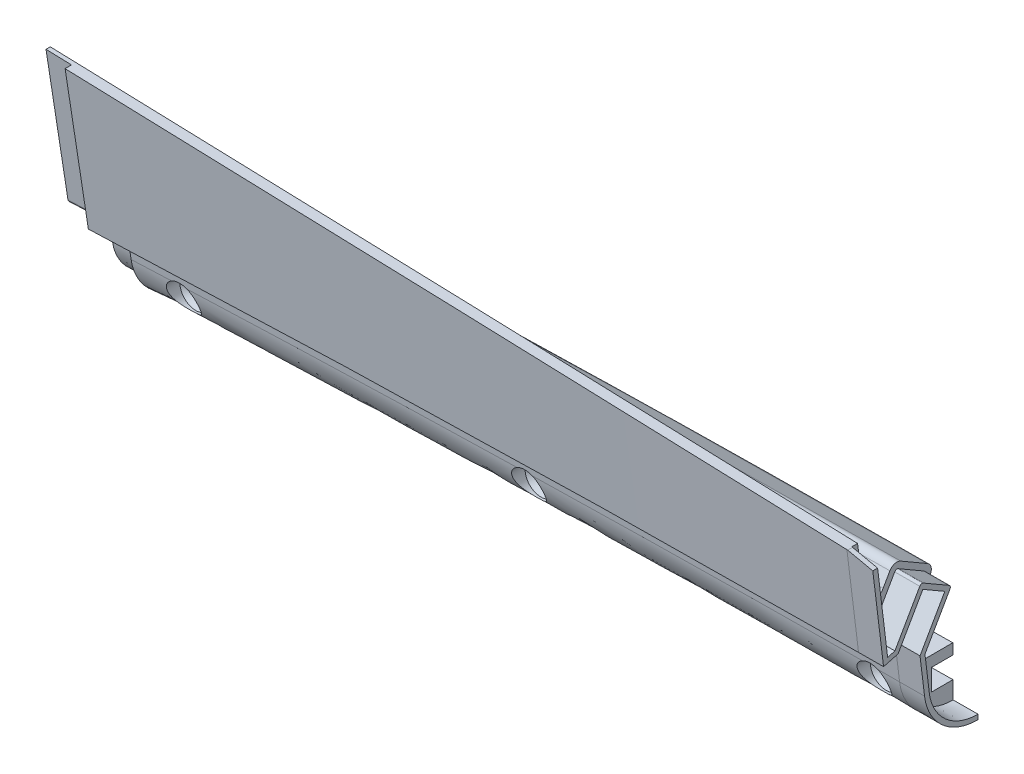
SolidWorks part; units mm, degrees
ref_plane "Front Plane" through (0, 0, 0) normal (0, 0, 1) x (1, 0, 0)
ref_plane "Top Plane" through (0, 0, 0) normal (0, 1, 0) x (1, 0, 0)
ref_plane "Right Plane" through (0, 0, 0) normal (1, 0, 0) x (0, 0, -1)
ref_plane "Plane3" through (-117.056, -3.871, 0) normal (0.9995, 0.0331, 0) x (0, 0, -1)
sketch "Sketch2" plane through (-117.056, -3.871, 0) normal (0.9995, 0.0331, 0) x (0, 0, -1)
  line L0 (-101.6, -41.1511) -> (-101.6, -45.9265)
  line L1 (-101.6, -41.1511) -> (-101.6, -45.9265)
  line L2 (-106.68, -45.9265) -> (-106.68, -50.6257)
  line L3 (-106.68, -45.9265) -> (-106.68, -50.6257)
  line L4 (-101.6, -50.6257) -> (-106.68, -50.6257)
  line L5 (-101.6, -50.6257) -> (-106.68, -50.6257)
  line L6 (-101.6, -50.6257) -> (-101.6, -56.1377)
  line L7 (-101.6, -50.6257) -> (-101.6, -56.1377)
  line L8 (-106.68, -45.9265) -> (-101.6, -45.9265)
  line L9 (-106.68, -45.9265) -> (-101.6, -45.9265)
  line L10 (-106.8705, -50.8162) -> (-108.9961, -53.9781) construction
  line L11 (-101.7905, -43.196) -> (-101.7905, -45.736)
  line L12 (-106.8705, -45.736) -> (-101.7905, -45.736)
  line L13 (-106.8705, -45.736) -> (-106.8705, -50.8162)
  line L14 (-101.7905, -50.8162) -> (-106.8705, -50.8162)
  line L15 (-101.7905, -50.8162) -> (-101.7905, -56.1377)
  line L16 (-101.7905, -43.196) -> (-101.6, -43.196)
  line L17 (-101.7905, -41.1511) -> (-101.7905, -45.736) construction
  line L18 (-120.8053, -33.0481) -> (-115.57, -36.0708)
  line L19 (-120.8053, -33.0481) -> (-115.57, -36.0708)
  line L20 (-109.601, -25.7318) -> (-114.8363, -22.709)
  line L21 (-109.601, -25.7318) -> (-114.8363, -22.709)
  line L22 (-114.8363, -22.709) -> (-120.8053, -33.0481)
  line L23 (-114.8363, -22.709) -> (-120.8053, -33.0481)
  line L24 (-115.57, -36.0708) -> (-109.601, -25.7318)
  line L25 (-115.57, -36.0708) -> (-109.601, -25.7318)
  line L26 (-115.57, -36.0708) -> (-114.523, -44.9291)
  line L28 (-118.1876, -34.5595) -> (-112.2186, -24.2204) construction
  line L29 (-114.6403, -39.5406) -> (-107.0838, -26.4518)
  line L30 (-107.7811, -23.8496) -> (-114.1162, -20.1918)
  line L31 (-116.7185, -20.8891) -> (-124.2749, -33.9778)
  line L33 (-106.1314, -24.8021) -> (-115.766, -19.2393) construction
  line L34 (-115.766, -19.2393) -> (-124.2749, -33.9778) construction
  line L35 (-114.6403, -39.5406) -> (-106.1314, -24.8021) construction
  line L36 (-124.2749, -33.9778) -> (-114.6403, -39.5406) construction
  line L37 (-112.9486, -36.6103) -> (-112.1701, -43.196)
  line L38 (-124.2749, -33.9778) -> (-128.0422, -2.1051)
  line L39 (-128.0422, -2.1051) -> (-132.6063, -0.4439)
  line L40 (-50.8, 0.7495) -> (-2184.4, 0.7495)
  line L41 (-125.822, 0.7495) -> (-133.442, 0.7495)
  line L42 (-122.1519, -30.3004) -> (-125.822, 0.7495)
  arc A0 (-114.523, -44.9291) -> (-101.7905, -56.1377) centre (-101.9108, -43.4383) ccw
  arc A2 (-114.1162, -20.1918) -> (-116.7185, -20.8891) centre (-115.0687, -21.8416) ccw
  arc A3 (-107.0838, -26.4518) -> (-107.7811, -23.8496) centre (-108.7336, -25.4993) ccw
  arc A4 (-133.442, 0.7495) -> (-132.6063, -0.4439) centre (-132.172, 0.7495) ccw
  point P41 (-133.442, 0.7495)
  dimension "D2" = 25.4
  dimension "D6" = 1.905
  dimension "D8" = 2.54
  dimension "D4" = 2.54
  dimension "D5" = 2.54
  dimension "D7" = 2.54
  dimension "D9" = 2.54
  dimension "D10" = 20
  dimension "D11" = 7.62
  dimension "D12" = 3.81
  dimension "D3" = 0.1905
sketch "Sketch3" plane through (0, 0, 101.6) normal (0, 0, 1) x (1, 0, 0)
  arc A0 (622.1039, -83.1998) -> (-622.1039, -83.1998) centre (0, -4954.4862) ccw construction
  arc A1 (622.1039, -83.1998) -> (-622.1039, -83.1998) centre (0, -4954.4862) ccw
sketch "Sketch4" plane through (-117.3306, 4.4304, 1117.6) normal (0.9995, 0.0331, 0) x (0, 0, -1)
  line L29 (1009.8189, -32.1556) -> (1003.4838, -28.4978) construction
  line L32 (1000.8815, -29.1951) -> (993.3251, -42.2838) construction
  line L35 (993.3251, -42.2838) -> (989.5578, -10.4111) construction
  line L50 (995.4481, -38.6064) -> (991.778, -7.5565) construction
  line L51 (1002.03, -44.3768) -> (1003.077, -53.235) construction
  line L52 (1015.8095, -59.1222) -> (1015.8095, -64.4437) construction
  line L53 (1015.8095, -59.1222) -> (1010.7295, -59.1222) construction
  line L54 (1010.7295, -54.042) -> (1010.7295, -59.1222) construction
  line L55 (1010.7295, -54.042) -> (1015.8095, -54.042) construction
  line L56 (1015.8095, -51.502) -> (1015.8095, -54.042) construction
  line L57 (1015.8095, -51.502) -> (1016, -51.502) construction
  line L58 (1004.6514, -44.9163) -> (1005.4299, -51.502) construction
  line L60 (1002.7637, -31.015) -> (996.7947, -41.3541) construction
  line L61 (1007.999, -34.0377) -> (1002.7637, -31.015) construction
  line L62 (1002.03, -44.3768) -> (1007.999, -34.0377) construction
  line L64 (991.5295, -5.4538) -> (988.9718, -5.4538)
  line L69 (1009.8189, -32.1556) -> (1003.4838, -28.4978)
  line L70 (1000.8815, -29.1951) -> (999.2724, -31.9822)
  line L71 (993.3251, -42.2838) -> (988.9718, -5.4538)
  line L74 (994.5502, -31.0104) -> (991.5295, -5.4538)
  line L75 (1002.03, -44.3768) -> (1003.077, -53.235)
  line L76 (1015.8095, -59.1222) -> (1015.8095, -64.4437)
  line L77 (1015.8095, -59.1222) -> (1010.7295, -59.1222)
  line L78 (1010.7295, -54.042) -> (1010.7295, -59.1222)
  line L79 (1010.7295, -54.042) -> (1015.8095, -54.042)
  line L80 (1015.8095, -51.502) -> (1015.8095, -54.042)
  line L81 (1015.8095, -51.502) -> (1007.6873, -51.502)
  line L82 (1004.7505, -45.7539) -> (1005.1649, -49.2601)
  line L84 (1002.7637, -31.015) -> (996.7947, -41.3541)
  line L85 (1007.999, -34.0377) -> (1002.7637, -31.015)
  line L86 (1002.03, -44.3768) -> (1007.999, -34.0377)
  line L87 (996.7947, -41.3541) -> (993.3251, -42.2838)
  line L88 (1005.0732, -44.1858) -> (1010.5162, -34.7578)
  arc A8 (1010.5162, -34.7578) -> (1009.8189, -32.1556) centre (1008.8664, -33.8053) ccw construction
  arc A9 (1003.4838, -28.4978) -> (1000.8815, -29.1951) centre (1002.5313, -30.1476) ccw construction
  arc A11 (1003.077, -53.235) -> (1015.8095, -64.4437) centre (1015.6892, -51.7443) ccw construction
  arc A12 (1010.5162, -34.7578) -> (1009.8189, -32.1556) centre (1008.8664, -33.8053) ccw
  arc A13 (1003.4838, -28.4978) -> (1000.8815, -29.1951) centre (1002.5313, -30.1476) ccw
  arc A15 (1003.077, -53.235) -> (1015.8095, -64.4437) centre (1015.6892, -51.7443) ccw
  arc A16 (1005.1649, -49.2601) -> (1007.6873, -51.502) centre (1007.6873, -48.962) ccw
  arc A17 (1004.7505, -45.7539) -> (1005.0732, -44.1858) centre (1007.2729, -45.4558) cw
  arc A18 (994.5502, -31.0104) -> (999.2724, -31.9822) centre (997.0727, -30.7122) ccw
  dimension "D2" = 2.54
  dimension "D1" = 36.83
sweep "Sweep3" add profiles "Sketch4" path "Sketch3"
sketch "Sketch5" plane through (0, 0, 101.7905) normal (0, 0, -1) x (-1, 0, 0)
  line L0 (211.6509, -4.1577) -> (0, -4954.4862) construction
  line L1 (0, -4954.4862) -> (26.0737, -15.25) construction
  line L2 (117.0808, -1.0187) -> (0, -4954.4862) construction
  arc A1 (628.0925, -39.606) -> (-627.2635, -39.5001) centre (0, -4954.4862) ccw construction
  point P16 (117.0808, -1.0187)
ref_plane "Plane1" through (-211.4422, -9.0402, 0) normal (-0.9991, -0.0427, 0) x (0.0427, -0.9991, 0)
ref_plane "Plane2" through (-26.1535, -0.1381, 0) normal (1, 0.0053, 0) x (-0.0053, 1, 0)
other "SurfaceCut1"
other "SurfaceCut2"
sketch "Sketch8" plane through (-117.056, -3.871, 0) normal (0.9995, 0.0331, 0) x (0, 0, -1)
  line L0 (-106.8705, -50.8162) -> (-106.8705, -45.736)
  line L1 (-106.8705, -50.8162) -> (-106.8705, -45.736)
  line L2 (-106.8705, -48.2761) -> (-119.5705, -48.2761)
  line L3 (-119.5705, -48.2761) -> (-119.5705, -44.4661)
  line L4 (-119.5705, -44.4661) -> (-110.6805, -44.4661)
  line L5 (-110.6805, -44.4661) -> (-108.7755, -46.3711)
  line L6 (-108.7755, -46.3711) -> (-106.8705, -46.3711)
  line L7 (-119.5705, -48.2761) -> (-117.7248, -48.2761) construction
  dimension "D1" = 1.905
  dimension "D2" = 1.905
  dimension "D3" = 12.7
  dimension "D4" = 45
  dimension "D5" = 3.81
revolve "Cut-Revolve1" cut sketch "Sketch8" angle 360 about L7
sketch "Sketch9" plane through (0, 0, 106.8705) normal (0, 0, -1) x (-1, 0, 0)
  line L0 (198.0737, -52.2212) -> (197.8686, -57.297) construction
  line L1 (32.934, -48.3318) -> (32.8999, -53.4117) construction
  arc A1 (209.5755, -52.6994) -> (25.8993, -48.2896) centre (0, -4954.4862) ccw construction
  arc A2 (209.3585, -57.7748) -> (25.8725, -53.3695) centre (0, -4954.4862) ccw construction
  point P8 (197.9712, -54.7591)
  point P11 (0, -4954.4862)
  point P16 (115.4604, -52.1207)
  dimension "D1" = 82.55
  dimension "D2" = 82.55
sketch "Sketch10" plane through (0, 0, 106.8705) normal (0, 0, -1) x (-1, 0, 0)
  line L0 (32.934, -48.3318) -> (32.8999, -53.4117) construction
  point P0 (32.917, -50.8717)
  point P1 (197.9712, -54.7591)
pattern_sketch "Sketch-Pattern1" of "Cut-Revolve1" driven by "Sketch10"
sketch "Sketch12" plane through (0, 0, 101.7905) normal (0, 0, -1) x (-1, 0, 0)
  line L0 (25.9127, -45.7498) -> (0, -4954.4862) construction
  line L1 (0, -4954.4862) -> (19.9437, -45.7219) construction
  arc A1 (209.684, -50.1619) -> (25.9127, -45.7498) centre (0, -4954.4862) ccw construction
  arc A2 (25.9127, -45.7498) -> (19.9437, -45.7219) centre (0, -4954.4862) ccw
  dimension "D1" = 5.969
sketch "Sketch11" plane through (-26.1535, -0.1381, 0) normal (1, 0.0053, 0) x (0, 0, -1)
  line L6 (-101.7905, -53.2322) -> (-101.7905, -58.5535) construction
  line L10 (-128.6282, 0.4338) -> (-126.0705, 0.4338) construction
  line L11 (-124.2749, -36.3946) -> (-128.6282, 0.4338) construction
  line L12 (-120.8053, -35.4649) -> (-124.2749, -36.3946) construction
  line L13 (-114.8363, -25.1263) -> (-120.8053, -35.4649) construction
  line L14 (-109.601, -28.1489) -> (-114.8363, -25.1263) construction
  line L15 (-115.57, -38.4875) -> (-109.601, -28.1489) construction
  line L16 (-114.523, -47.3454) -> (-115.57, -38.4875) construction
  line L17 (-101.7905, -57.4106) -> (-101.7905, -58.5535)
  line L18 (-128.6282, 0.4338) -> (-127.4772, 0.4338)
  line L25 (-124.2749, -36.3946) -> (-128.6282, 0.4338)
  line L26 (-120.8053, -35.4649) -> (-124.2749, -36.3946)
  line L27 (-114.8363, -25.1263) -> (-120.8053, -35.4649)
  line L29 (-109.601, -28.1489) -> (-114.8363, -25.1263)
  line L30 (-115.57, -38.4875) -> (-109.601, -28.1489)
  line L31 (-114.523, -47.3454) -> (-115.57, -38.4875)
  line L32 (-113.3879, -47.2112) -> (-114.3903, -38.7303)
  line L33 (-114.3903, -38.7303) -> (-108.3571, -28.2805)
  line L34 (-108.5896, -27.4131) -> (-114.7047, -23.8825)
  line L35 (-115.5722, -24.1149) -> (-121.5584, -34.4834)
  line L54 (-121.5584, -34.4834) -> (-123.2949, -34.9487)
  line L55 (-123.2949, -34.9487) -> (-127.4772, 0.4338)
  line L56 (-101.8013, -57.4106) -> (-101.7905, -57.4106)
  line L57 (-123.2949, -34.9487) -> (-127.4931, 0.568) construction
  line L58 (-114.3903, -38.7303) -> (-108.0396, -27.7306) construction
  line L59 (-108.0396, -27.7306) -> (-115.2547, -23.565) construction
  line L60 (-115.2547, -23.565) -> (-121.5584, -34.4834) construction
  arc A2 (-108.3571, -28.2805) -> (-108.5896, -27.4131) centre (-108.9071, -27.963) ccw
  arc A3 (-114.7047, -23.8825) -> (-115.5722, -24.1149) centre (-115.0222, -24.4324) ccw
  spline S0 degree 3 poles (369.46, 1883.5044) (53.4107, 251.0151) (-51.656, -67.5371) (-104.4782, -58.2978) (-104.8546, -58.2143) (-105.6018, -58.0121) (-105.9744, -57.8927) (-107.0674, -57.4861) (-107.762, -57.1522) (-108.7542, -56.5596) (-109.0766, -56.3467) (-109.7043, -55.8893) (-110.0099, -55.6443) (-110.8822, -54.8766) (-111.4114, -54.3174) (-112.3662, -53.1048) (-112.7943, -52.4449) (-113.513, -51.0771) (-113.8076, -50.3659) (-114.1523, -49.2581) (-114.2511, -48.8807) (-128.7728, 19.3226) (415.3179, 185.4408) (1806.7101, 500.6763) knots -8.519335 -8.519335 -8.519335 -8.519335 0.125 0.125 0.1875 0.1875 0.25 0.25 0.375 0.375 0.4375 0.4375 0.5 0.5 0.625 0.625 0.75 0.75 0.875 0.875 0.9375 0.9375 12.048429 12.048429 12.048429 12.048429 only from (-101.7905, -58.5535) to (-114.523, -47.3454) construction
  spline S1 degree 3 poles (-101.7905, -58.5535) (-102.5713, -58.5609) (-103.3407, -58.4968) (-104.4782, -58.2978) (-104.8546, -58.2143) (-105.6018, -58.0121) (-105.9744, -57.8927) (-107.0674, -57.4861) (-107.762, -57.1522) (-108.7542, -56.5596) (-109.0766, -56.3467) (-109.7043, -55.8893) (-110.0099, -55.6443) (-110.8822, -54.8766) (-111.4114, -54.3174) (-112.3662, -53.1048) (-112.7943, -52.4449) (-113.513, -51.0771) (-113.8076, -50.3659) (-114.1523, -49.2581) (-114.2511, -48.8807) (-114.4136, -48.1177) (-114.4771, -47.7331) (-114.523, -47.3454) knots 0 0 0 0 0.125 0.125 0.1875 0.1875 0.25 0.25 0.375 0.375 0.4375 0.4375 0.5 0.5 0.625 0.625 0.75 0.75 0.875 0.875 0.9375 0.9375 1 1 1 1
  spline S2 degree 1 poles (-101.8013, -57.4106) (-113.3879, -47.2112) knots 0 0 1 1 construction
  spline S3 degree 3 poles (-101.8013, -57.4106) (-103.2019, -57.4238) (-106.0351, -56.929) (-109.7159, -54.7282) (-111.9316, -51.9047) (-113.0054, -49.3139) (-113.3048, -47.914) (-113.3879, -47.2112) knots 0 0 0 0 0.25 0.5 0.75 0.875 1 1 1 1
  dimension "D2" = 0.635
  dimension "D1" = 1.143
sweep "Sweep4" add profiles "Sketch11" path "Sketch12"
sketch "Sketch14" plane through (-211.4422, -9.0402, 0) normal (-0.9991, -0.0427, 0) x (0, 0, 1)
  line L0 (113.0095, -42.7133) -> (113.9971, -34.3581)
  line L1 (113.9971, -34.3581) -> (107.5192, -23.138)
  line L2 (107.5192, -23.138) -> (115.3941, -18.5914)
  line L3 (115.3941, -18.5914) -> (121.8095, -29.7031)
  line L4 (121.8095, -29.7031) -> (122.9682, -30.0136)
  line L5 (122.9682, -30.0136) -> (127.1147, 5.0658)
  line L18 (128.6282, 4.8869) -> (126.0705, 4.8869)
  line L19 (126.0705, 4.8869) -> (123.0498, -20.6686)
  line L20 (118.3276, -21.6403) -> (116.7185, -18.8534)
  line L21 (114.1162, -18.1561) -> (107.7811, -21.8137)
  line L22 (107.0838, -24.4158) -> (112.5268, -33.8434)
  line L23 (112.8495, -35.4115) -> (112.4351, -38.9175)
  line L24 (109.9127, -41.1592) -> (101.7905, -41.1592)
  line L25 (101.7905, -41.1592) -> (101.7905, -43.6991)
  line L26 (101.7905, -43.6991) -> (106.8705, -43.6991)
  line L27 (106.8705, -43.6991) -> (106.8705, -48.7791)
  line L28 (106.8705, -48.7791) -> (101.7905, -48.7791)
  line L29 (101.7905, -48.7791) -> (101.7905, -54.1004)
  line L30 (114.523, -42.8922) -> (115.57, -34.0344)
  line L31 (115.57, -34.0344) -> (109.601, -23.6958)
  line L32 (109.601, -23.6958) -> (114.8363, -20.6732)
  line L33 (114.8363, -20.6732) -> (120.8053, -31.0118)
  line L34 (120.8053, -31.0118) -> (124.2749, -31.9414)
  line L35 (124.2749, -31.9414) -> (128.6282, 4.8869)
  line L36 (128.6282, 4.8869) -> (126.0705, 4.8869)
  line L37 (126.0705, 4.8869) -> (123.0498, -20.6686)
  line L38 (118.3276, -21.6403) -> (116.7185, -18.8534)
  line L39 (114.1162, -18.1561) -> (107.7811, -21.8137)
  line L40 (107.0838, -24.4158) -> (112.5268, -33.8434)
  line L41 (112.8495, -35.4115) -> (112.4351, -38.9175)
  line L42 (109.9127, -41.1592) -> (101.7905, -41.1592)
  line L43 (101.7905, -41.1592) -> (101.7905, -43.6991)
  line L44 (101.7905, -43.6991) -> (106.8705, -43.6991)
  line L45 (106.8705, -43.6991) -> (106.8705, -48.7791)
  line L46 (106.8705, -48.7791) -> (101.7905, -48.7791)
  line L47 (101.7905, -48.7791) -> (101.7905, -54.1004)
  line L48 (114.523, -42.8922) -> (115.57, -34.0344)
  line L49 (115.57, -34.0344) -> (109.601, -23.6958)
  line L50 (109.601, -23.6958) -> (114.8363, -20.6732)
  line L51 (114.8363, -20.6732) -> (120.8053, -31.0118)
  line L52 (120.8053, -31.0118) -> (124.2749, -31.9414)
  line L53 (124.2749, -31.9414) -> (128.6282, 4.8869)
  arc A4 (116.7185, -18.8534) -> (114.1162, -18.1561) centre (115.0687, -19.8059) ccw
  arc A5 (107.7811, -21.8137) -> (107.0838, -24.4158) centre (108.7335, -23.4634) ccw
  arc A6 (112.8495, -35.4115) -> (112.5268, -33.8434) centre (110.3273, -35.1133) ccw
  arc A7 (109.9127, -41.1592) -> (112.4351, -38.9175) centre (109.9127, -38.6193) ccw
  arc A8 (116.7185, -18.8534) -> (114.1162, -18.1561) centre (115.0687, -19.8059) ccw
  arc A9 (107.7811, -21.8137) -> (107.0838, -24.4158) centre (108.7335, -23.4634) ccw
  arc A10 (112.8495, -35.4115) -> (112.5268, -33.8434) centre (110.3273, -35.1133) ccw
  arc A11 (109.9127, -41.1592) -> (112.4351, -38.9175) centre (109.9127, -38.6193) ccw
  spline S0 degree 1 poles (101.8049, -52.5765) (113.0095, -42.7133) knots 0 0 1 1 construction
  spline S1 degree 3 poles (101.8049, -52.5765) (102.4893, -52.583) (103.8689, -52.4674) (106.4858, -51.7551) (109.4658, -49.9761) (112.0284, -46.7154) (112.8505, -44.0584) (113.0095, -42.7133) knots 0 0 0 0 0.125 0.25 0.5 0.75 1 1 1 1
  spline S2 degree 3 poles (-1420.2451, -2589.1907) (7.5348, 76.4537) (129.3579, -7.252) (122.7249, -21.671) (122.575, -21.8961) (122.2185, -22.2837) (122.0069, -22.4517) (121.6628, -22.6462) (121.5435, -22.702) (121.2955, -22.795) (121.1665, -22.8321) (120.908, -22.8851) (120.7774, -22.9014) (120.5134, -22.9137) (120.3791, -22.9094) (120.1163, -22.8803) (119.987, -22.8557) (119.7325, -22.7864) (119.6063, -22.7412) (119.2436, -22.578) (119.0214, -22.433) (93.7379, 0.421) (581.1886, 448.0858) (2362.312, 1968.4478) knots -7.286241 -7.286241 -7.286241 -7.286241 0.125 0.125 0.25 0.25 0.375 0.375 0.4375 0.4375 0.5 0.5 0.5625 0.5625 0.625 0.625 0.6875 0.6875 0.75 0.75 0.875 0.875 16.766809 16.766809 16.766809 16.766809 only from (123.0498, -20.6686) to (118.3276, -21.6403)
  spline S3 degree 3 poles (-288.3388, 2916.9987) (-102.777, 757.3692) (19.5454, -60.9671) (103.3479, -54.0254) (103.7348, -53.9753) (104.8774, -53.7738) (105.6202, -53.5717) (107.068, -53.0324) (107.777, -52.6914) (109.1008, -51.8981) (109.7227, -51.4442) (110.5948, -50.6762) (110.8766, -50.4042) (111.4099, -49.8396) (111.662, -49.5468) (112.3757, -48.6378) (112.795, -47.9912) (113.3369, -46.9586) (113.5026, -46.6041) (113.7979, -45.8886) (113.9285, -45.5258) (132.5439, 14.5864) (-288.4354, 203.7302) (-2703.1014, 979.8882) knots -13.349036 -13.349036 -13.349036 -13.349036 0.0625 0.0625 0.125 0.125 0.25 0.25 0.375 0.375 0.5 0.5 0.5625 0.5625 0.625 0.625 0.75 0.75 0.8125 0.8125 0.875 0.875 11.030088 11.030088 11.030088 11.030088 only from (101.7905, -54.1004) to (114.523, -42.8922)
  spline S4 degree 3 poles (123.0498, -20.6686) (123.0184, -20.9338) (122.9449, -21.1927) (122.7249, -21.671) (122.575, -21.8961) (122.2185, -22.2837) (122.0069, -22.4517) (121.6628, -22.6462) (121.5435, -22.702) (121.2955, -22.795) (121.1665, -22.8321) (120.908, -22.8851) (120.7774, -22.9014) (120.5134, -22.9137) (120.3791, -22.9094) (120.1163, -22.8803) (119.987, -22.8557) (119.7325, -22.7864) (119.6063, -22.7412) (119.2436, -22.578) (119.0214, -22.433) (118.6267, -22.0763) (118.4611, -21.8716) (118.3276, -21.6403) knots 0 0 0 0 0.125 0.125 0.25 0.25 0.375 0.375 0.4375 0.4375 0.5 0.5 0.5625 0.5625 0.625 0.625 0.6875 0.6875 0.75 0.75 0.875 0.875 1 1 1 1
  spline S5 degree 3 poles (101.7905, -54.1004) (102.1809, -54.1041) (102.5705, -54.0898) (103.3479, -54.0254) (103.7348, -53.9753) (104.8774, -53.7738) (105.6202, -53.5717) (107.068, -53.0324) (107.777, -52.6914) (109.1008, -51.8981) (109.7227, -51.4442) (110.5948, -50.6762) (110.8766, -50.4042) (111.4099, -49.8396) (111.662, -49.5468) (112.3757, -48.6378) (112.795, -47.9912) (113.3369, -46.9586) (113.5026, -46.6041) (113.7979, -45.8886) (113.9285, -45.5258) (114.2702, -44.4227) (114.4313, -43.6677) (114.523, -42.8922) knots 0 0 0 0 0.0625 0.0625 0.125 0.125 0.25 0.25 0.375 0.375 0.5 0.5 0.5625 0.5625 0.625 0.625 0.75 0.75 0.8125 0.8125 0.875 0.875 1 1 1 1
  dimension "D1" = 0
  dimension "D2" = 1.524
sketch "Sketch15" plane through (-211.4422, -9.0402, 0) normal (-0.9991, -0.0427, 0) x (0, 0, 1)
  line L0 (113.0095, -42.7133) -> (113.9971, -34.3581) construction
  line L1 (113.9971, -34.3581) -> (107.5192, -23.138) construction
  line L2 (107.5192, -23.138) -> (115.3941, -18.5914) construction
  line L3 (115.3941, -18.5914) -> (121.8095, -29.7031) construction
  line L4 (121.8095, -29.7031) -> (122.9682, -30.0136) construction
  line L5 (122.9682, -30.0136) -> (127.1147, 5.0658) construction
  line L6 (113.0095, -42.7133) -> (113.9724, -34.5675)
  line L7 (113.8917, -34.1755) -> (107.5192, -23.138)
  line L8 (107.5192, -23.138) -> (115.3941, -18.5914)
  line L9 (115.3941, -18.5914) -> (121.678, -29.4753)
  line L10 (122.0636, -29.7712) -> (122.2594, -29.8237)
  line L11 (123.0543, -29.2848) -> (127.0936, 4.8869)
  line L12 (101.7905, -48.7791) -> (101.7905, -54.1004) construction
  line L13 (101.7905, -48.7791) -> (101.7905, -52.5765)
  line L14 (101.8049, -52.5765) -> (101.7905, -52.5765)
  line L18 (124.2749, -31.9414) -> (128.6282, 4.8869)
  line L19 (128.6282, 4.8869) -> (126.0705, 4.8869)
  line L20 (126.0705, 4.8869) -> (123.0498, -20.6686)
  line L21 (118.3276, -21.6403) -> (116.7185, -18.8534)
  line L22 (114.1162, -18.1561) -> (107.7811, -21.8137)
  line L23 (107.0838, -24.4158) -> (112.5268, -33.8434)
  line L24 (112.8495, -35.4115) -> (112.4351, -38.9175)
  line L25 (109.9127, -41.1592) -> (101.7905, -41.1592)
  line L26 (101.7905, -41.1592) -> (101.7905, -43.6991)
  line L27 (101.7905, -43.6991) -> (106.8705, -43.6991)
  line L28 (106.8705, -43.6991) -> (106.8705, -48.7791)
  line L29 (106.8705, -48.7791) -> (101.7905, -48.7791)
  line L30 (101.7905, -48.7791) -> (101.7905, -54.1004)
  line L31 (114.523, -42.8922) -> (115.57, -34.0344)
  line L32 (115.57, -34.0344) -> (109.601, -23.6958)
  line L33 (109.601, -23.6958) -> (114.8363, -20.6732)
  line L34 (114.8363, -20.6732) -> (120.8053, -31.0118)
  line L35 (120.8053, -31.0118) -> (124.2749, -31.9414)
  line L37 (127.0936, 4.8869) -> (126.0705, 4.8869)
  line L38 (126.0705, 4.8869) -> (123.0498, -20.6686)
  line L39 (118.3276, -21.6403) -> (116.7185, -18.8534)
  line L40 (114.1162, -18.1561) -> (107.7811, -21.8137)
  line L41 (107.0838, -24.4158) -> (112.5268, -33.8434)
  line L42 (112.8495, -35.4115) -> (112.4351, -38.9175)
  line L43 (109.9127, -41.1592) -> (101.7905, -41.1592)
  line L44 (101.7905, -41.1592) -> (101.7905, -43.6991)
  line L45 (101.7905, -43.6991) -> (106.8705, -43.6991)
  line L46 (106.8705, -43.6991) -> (106.8705, -48.7791)
  line L47 (106.8705, -48.7791) -> (101.7905, -48.7791)
  arc A0 (113.9724, -34.5675) -> (113.8917, -34.1755) centre (113.3418, -34.493) ccw
  arc A1 (121.678, -29.4753) -> (122.0636, -29.7712) centre (122.2279, -29.1578) ccw
  arc A2 (122.2594, -29.8237) -> (123.0543, -29.2848) centre (122.4237, -29.2103) ccw
  arc A4 (116.7185, -18.8534) -> (114.1162, -18.1561) centre (115.0687, -19.8059) ccw
  arc A5 (107.7811, -21.8137) -> (107.0838, -24.4158) centre (108.7335, -23.4634) ccw
  arc A6 (112.8495, -35.4115) -> (112.5268, -33.8434) centre (110.3273, -35.1133) ccw
  arc A7 (109.9127, -41.1592) -> (112.4351, -38.9175) centre (109.9127, -38.6193) ccw
  arc A8 (116.7185, -18.8534) -> (114.1162, -18.1561) centre (115.0687, -19.8059) ccw
  arc A9 (107.7811, -21.8137) -> (107.0838, -24.4158) centre (108.7335, -23.4634) ccw
  arc A10 (112.8495, -35.4115) -> (112.5268, -33.8434) centre (110.3273, -35.1133) ccw
  arc A11 (109.9127, -41.1592) -> (112.4351, -38.9175) centre (109.9127, -38.6193) ccw
  spline S0 degree 3 poles (1969.6766, 654.3437) (8.5109, 56.766) (75.3403, -60.2329) (106.4858, -51.7551) (109.4658, -49.9761) (134.2797, -18.4018) (-16.091, 107.1074) (-926.156, -1745.3361) knots -5.450838 -5.450838 -5.450838 -5.450838 0.125 0.25 0.5 0.75 7.512309 7.512309 7.512309 7.512309 only from (101.8049, -52.5765) to (113.0095, -42.7133) construction
  spline S1 degree 3 poles (101.8049, -52.5765) (102.4893, -52.583) (103.8689, -52.4674) (106.4858, -51.7551) (109.4658, -49.9761) (112.0284, -46.7154) (112.8505, -44.0584) (113.0095, -42.7133) knots 0 0 0 0 0.125 0.25 0.5 0.75 1 1 1 1
  spline S2 degree 3 poles (-1420.2451, -2589.1907) (7.5348, 76.4537) (129.3579, -7.252) (122.7249, -21.671) (122.575, -21.8961) (122.2185, -22.2837) (122.0069, -22.4517) (121.6628, -22.6462) (121.5435, -22.702) (121.2955, -22.795) (121.1665, -22.8321) (120.908, -22.8851) (120.7774, -22.9014) (120.5134, -22.9137) (120.3791, -22.9094) (120.1163, -22.8803) (119.987, -22.8557) (119.7325, -22.7864) (119.6063, -22.7412) (119.2436, -22.578) (119.0214, -22.433) (93.7379, 0.421) (581.1886, 448.0858) (2362.312, 1968.4478) knots -7.286241 -7.286241 -7.286241 -7.286241 0.125 0.125 0.25 0.25 0.375 0.375 0.4375 0.4375 0.5 0.5 0.5625 0.5625 0.625 0.625 0.6875 0.6875 0.75 0.75 0.875 0.875 16.766809 16.766809 16.766809 16.766809 only from (123.0498, -20.6686) to (118.3276, -21.6403)
  spline S3 degree 3 poles (-93.3253, 926.6784) (-10.5613, 232.0775) (53.1389, -58.1844) (103.3479, -54.0254) (103.7348, -53.9753) (104.8774, -53.7738) (105.6202, -53.5717) (107.068, -53.0324) (107.777, -52.6914) (109.1008, -51.8981) (109.7227, -51.4442) (110.5948, -50.6762) (110.8766, -50.4042) (111.4099, -49.8396) (111.662, -49.5468) (112.3757, -48.6378) (112.795, -47.9912) (113.3369, -46.9586) (113.5026, -46.6041) (113.7979, -45.8886) (113.9285, -45.5258) (125.9187, -6.8076) (-43.2917, 84.8615) (-804.6708, 350.8867) knots -7.947776 -7.947776 -7.947776 -7.947776 0.0625 0.0625 0.125 0.125 0.25 0.25 0.375 0.375 0.5 0.5 0.5625 0.5625 0.625 0.625 0.75 0.75 0.8125 0.8125 0.875 0.875 7.39364 7.39364 7.39364 7.39364 only from (101.7905, -54.1004) to (114.523, -42.8922)
  spline S4 degree 3 poles (123.0498, -20.6686) (123.0184, -20.9338) (122.9449, -21.1927) (122.7249, -21.671) (122.575, -21.8961) (122.2185, -22.2837) (122.0069, -22.4517) (121.6628, -22.6462) (121.5435, -22.702) (121.2955, -22.795) (121.1665, -22.8321) (120.908, -22.8851) (120.7774, -22.9014) (120.5134, -22.9137) (120.3791, -22.9094) (120.1163, -22.8803) (119.987, -22.8557) (119.7325, -22.7864) (119.6063, -22.7412) (119.2436, -22.578) (119.0214, -22.433) (118.6267, -22.0763) (118.4611, -21.8716) (118.3276, -21.6403) knots 0 0 0 0 0.125 0.125 0.25 0.25 0.375 0.375 0.4375 0.4375 0.5 0.5 0.5625 0.5625 0.625 0.625 0.6875 0.6875 0.75 0.75 0.875 0.875 1 1 1 1
  dimension "D2" = 0.635
  dimension "D1" = 0
sketch "Sketch16" plane through (0, 0, 101.7905) normal (0, 0, -1) x (-1, 0, 0)
  arc A0 (215.6474, -50.4205) -> (209.684, -50.1619) centre (0, -4954.4862) ccw
  arc A1 (209.684, -50.1619) -> (25.9127, -45.7498) centre (0, -4954.4862) ccw construction
  dimension "D1" = 5.969
sweep "Sweep5" add profiles "Sketch15" path "Sketch16"
ref_plane "Plane4" through (-0.6113, -15.0156, 0) normal (-0.0407, -0.9992, 0) x (-0.9992, 0.0407, 0)
other "SurfaceCut3"
ref_plane "Plane5" through (-4.8813, -19.2999, 0) normal (-0.2452, -0.9695, 0) x (-0.9695, 0.2452, 0)
other "SurfaceCut4"
